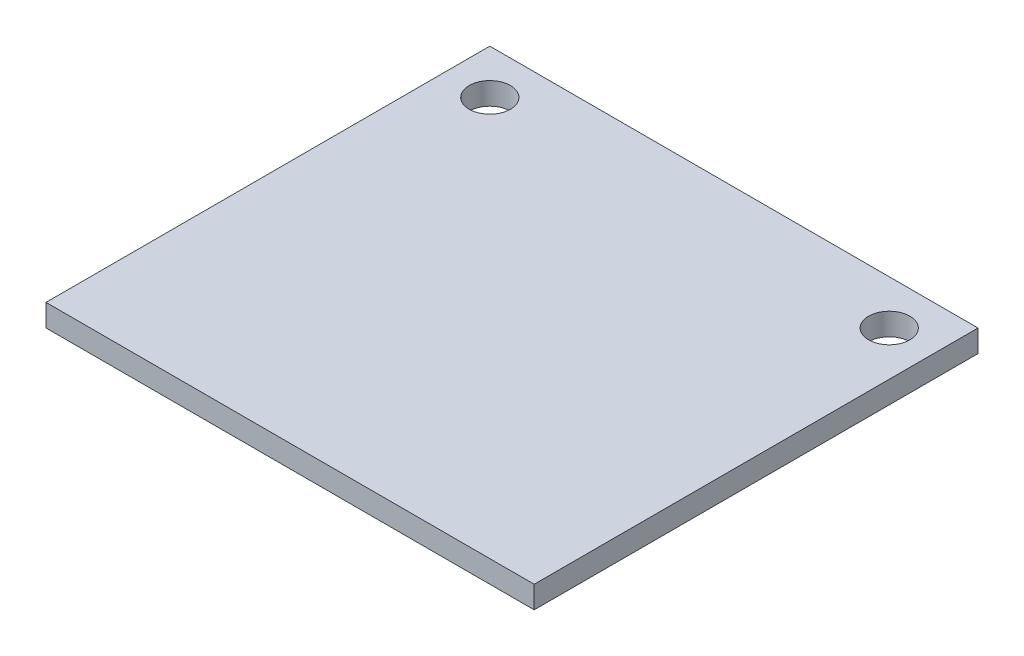
SolidWorks part; units mm, degrees
ref_plane "Front Plane" through (0, 0, 0) normal (0, 0, 1) x (1, 0, 0)
ref_plane "Top Plane" through (0, 0, 0) normal (0, 1, 0) x (1, 0, 0)
ref_plane "Right Plane" through (0, 0, 0) normal (1, 0, 0) x (0, 0, -1)
sketch "Sketch1" plane through (0, 0, 0) normal (0, 1, 0) x (1, 0, 0)
  line L1 (0, 0) -> (34.925, 0)
  line L2 (0, 0) -> (0, 31.75)
  line L3 (0, 31.75) -> (34.925, 31.75)
  line L4 (34.925, 0) -> (34.925, 31.75)
  dimension "D1" = 34.925
  dimension "D2" = 31.75
extrude "Boss-Extrude1" add sketch "Sketch1" along normal blind 1.5875
sketch "Sketch2" plane through (0, 1.5875, 0) normal (0, 1, 0) x (1, 0, 0)
  line L0 (0, 28.575) -> (34.925, 28.575) construction
  line L1 (0, 31.75) -> (0, 0) construction
  line L2 (34.925, 0) -> (34.925, 31.75) construction
  line L3 (34.925, 31.75) -> (0, 31.75) construction
  circle A0 centre (3.175, 28.575) radius 1.4732
  circle A1 centre (31.75, 28.575) radius 1.4732
  dimension "D2" = 2.9464
  dimension "D1" = 3.175
  dimension "D3" = 3.175
  dimension "D4" = 3.175
extrude "Cut-Extrude1" cut sketch "Sketch2" against normal blind 1.5875
